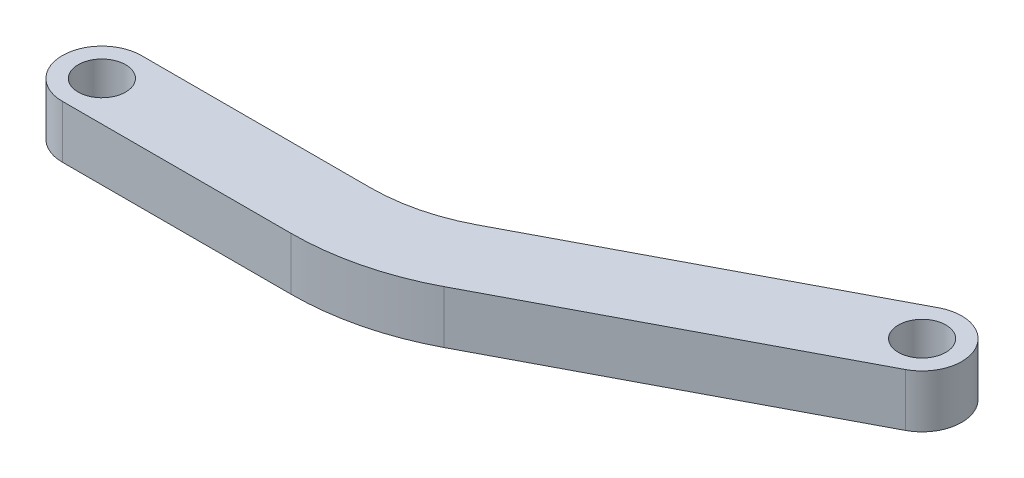
SolidWorks part; units mm, degrees
ref_plane "Alzado" through (0, 0, 0) normal (0, 0, 1) x (1, 0, 0)
ref_plane "Planta" through (0, 0, 0) normal (0, 1, 0) x (1, 0, 0)
ref_plane "Vista lateral" through (0, 0, 0) normal (1, 0, 0) x (0, 0, -1)
sketch "Sketch1" plane through (0, 0, 0) normal (0, 1, 0) x (1, 0, 0)
  line L0 (0, -4.5) -> (25.98, -4.5)
  line L1 (39.9304, -1.0591) -> (74.3426, 17.0161)
  line L2 (70.1574, 24.9839) -> (35.7453, 6.9086)
  line L3 (25.98, 4.5) -> (0, 4.5)
  arc A0 (0, 4.5) -> (0, -4.5) centre (0, 0) ccw
  arc A1 (25.98, -4.5) -> (39.9304, -1.0591) centre (25.98, 25.5) ccw
  arc A2 (74.3426, 17.0161) -> (70.1574, 24.9839) centre (72.25, 21) ccw
  arc A3 (35.7453, 6.9086) -> (25.98, 4.5) centre (25.98, 25.5) cw
  circle A4 centre (0, 0) radius 2.7
  circle A5 centre (72.25, 21) radius 2.7
  dimension "D1" = 25.98
  dimension "D2" = 72.25
  dimension "D3" = 9
  dimension "D6" = 30
  dimension "D4" = 5.4
  dimension "D7" = 21
extrude "Boss-Extrude1" add sketch "Sketch1" along normal blind 6
